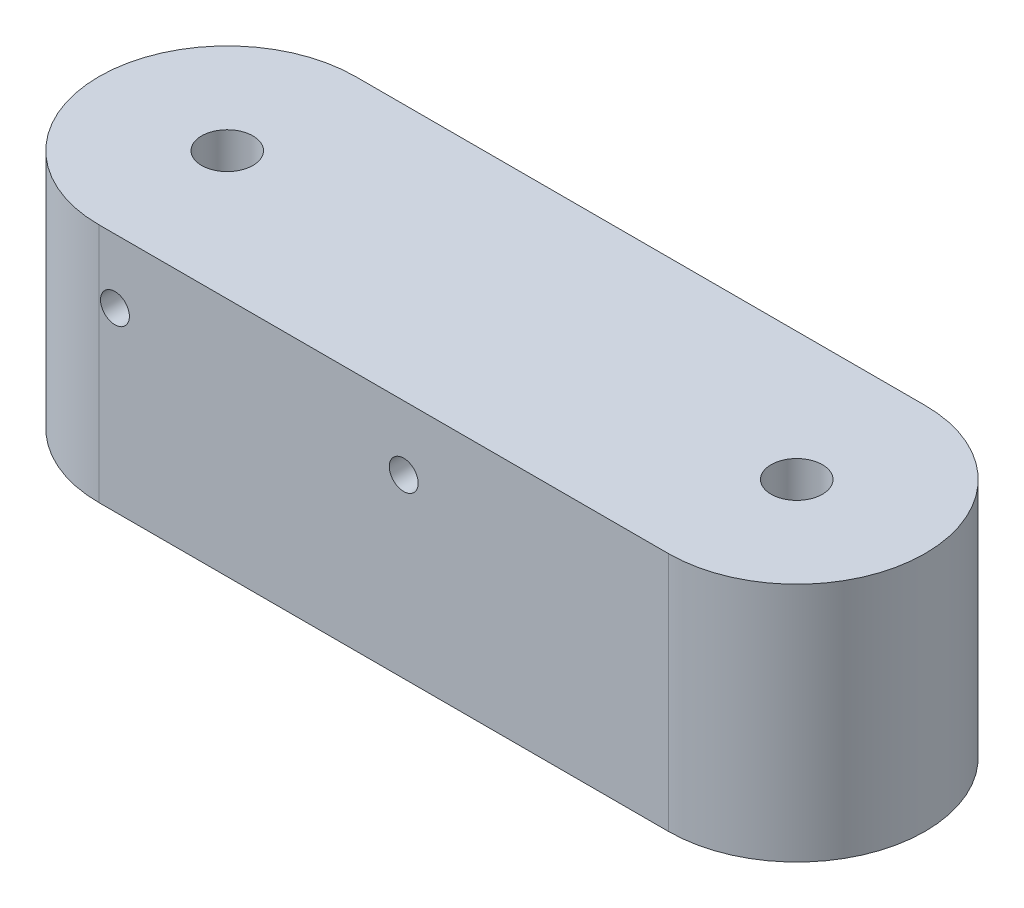
SolidWorks part; units mm, degrees
material "PLA"
ref_plane "前视基准面" through (0, 0, 0) normal (0, 0, 1) x (1, 0, 0)
ref_plane "上视基准面" through (0, 0, 0) normal (0, 1, 0) x (1, 0, 0)
ref_plane "右视基准面" through (0, 0, 0) normal (1, 0, 0) x (0, 0, -1)
sketch "草图1" plane through (0, 0, 0) normal (0, 1, 0) x (1, 0, 0)
  line L0 (0, 0) -> (35.5, 0) construction
  line L1 (0, 8) -> (35.5, 8)
  line L2 (0, -8) -> (35.5, -8)
  circle A0 centre (35.5, 0) radius 1.6
  circle A1 centre (0, 0) radius 1.6
  arc A2 (0, 8) -> (0, -8) centre (0, 0) ccw
  circle A3 centre (35.5, 0) radius 1.6
  arc A5 (35.5, -8) -> (35.5, 8) centre (35.5, 0) ccw
  dimension "D2" = 3.2
  dimension "D3" = 16
  dimension "D1" = 35.5
extrude "凸台-拉伸1" add sketch "草图1" along normal blind 15
sketch "草图2" plane through (0, 0, 8) normal (0, 0, 1) x (1, 0, 0)
  line L0 (1, 11) -> (19, 11) construction
  line L1 (0, 15) -> (35.5, 15) construction
  line L2 (0, 15) -> (0, 0) construction
  circle A0 centre (19, 11) radius 0.9
  circle A1 centre (1, 11) radius 0.9
  dimension "D1" = 1.8
  dimension "D4" = 1
  dimension "D2" = 18
  dimension "D3" = 4
extrude "切除-拉伸1" cut sketch "草图2" against normal through all
